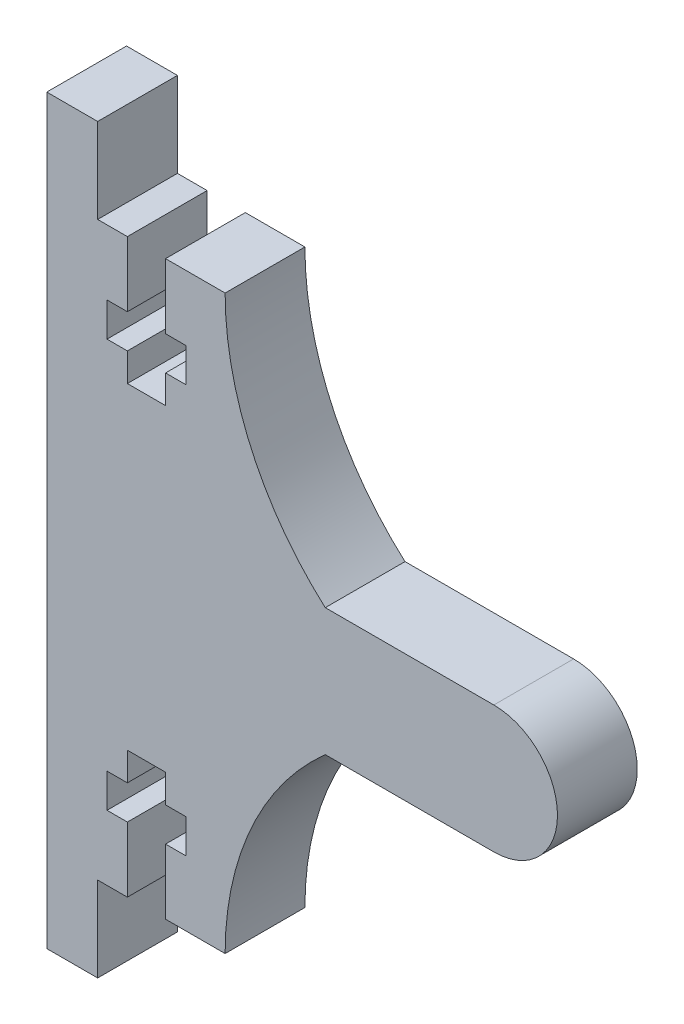
SolidWorks part; units mm, degrees
material "Acrylic (Medium-high impact)"
ref_plane "Front Plane" through (0, 0, 0) normal (0, 0, 1) x (1, 0, 0)
ref_plane "Top Plane" through (0, 0, 0) normal (0, 1, 0) x (1, 0, 0)
ref_plane "Right Plane" through (0, 0, 0) normal (1, 0, 0) x (0, 0, -1)
sketch "Sketch1" plane through (0, 0, 0) normal (0, 0, 1) x (1, 0, 0)
  line L0 (652.8999, 449.103) -> (640.9814, 449.103)
  line L1 (652.8999, 440.103) -> (640.9814, 440.103)
  line L2 (633.8999, 464.828) -> (633.8999, 424.378) construction
  line L3 (629.6883, 424.378) -> (633.8999, 424.378)
  line L4 (629.6883, 428.978) -> (629.6883, 424.378)
  line L5 (631.1282, 428.978) -> (629.6883, 428.978)
  line L6 (631.1282, 431.378) -> (631.1282, 428.978)
  line L7 (629.6883, 431.378) -> (631.1282, 431.378)
  line L8 (629.6883, 433.378) -> (629.6883, 431.378)
  line L9 (626.9883, 433.378) -> (629.6883, 433.378)
  line L10 (626.9883, 431.378) -> (626.9883, 433.378)
  line L11 (625.5484, 431.378) -> (626.9883, 431.378)
  line L12 (625.5484, 428.978) -> (625.5484, 431.378)
  line L13 (626.9883, 428.978) -> (625.5484, 428.978)
  line L14 (626.9883, 424.378) -> (626.9883, 428.978)
  line L15 (624.8883, 424.378) -> (626.9883, 424.378)
  line L16 (624.8883, 418.378) -> (624.8883, 424.378)
  line L17 (621.2883, 464.828) -> (621.2883, 470.828)
  line L18 (621.2883, 470.828) -> (624.8883, 470.828)
  line L19 (624.8883, 470.828) -> (624.8883, 464.828)
  line L20 (624.8883, 464.828) -> (626.9883, 464.828)
  line L21 (626.9883, 464.828) -> (626.9883, 460.228)
  line L22 (626.9883, 460.228) -> (625.5484, 460.228)
  line L23 (625.5484, 460.228) -> (625.5484, 457.8279)
  line L24 (625.5484, 457.8279) -> (626.9883, 457.8279)
  line L25 (626.9883, 457.8279) -> (626.9883, 455.8279)
  line L26 (626.9883, 455.8279) -> (629.6883, 455.8279)
  line L27 (629.6883, 455.8279) -> (629.6883, 457.8279)
  line L28 (629.6883, 457.8279) -> (631.1282, 457.8279)
  line L29 (631.1282, 457.8279) -> (631.1282, 460.228)
  line L30 (631.1282, 460.228) -> (629.6883, 460.228)
  line L31 (629.6883, 460.228) -> (629.6883, 464.828)
  line L32 (629.6883, 464.828) -> (633.8999, 464.828)
  line L33 (621.2883, 418.378) -> (624.8883, 418.378)
  line L34 (-348.8277, 444.603) -> (49651.1723, 444.603) construction
  line L35 (628.3383, -544.1471) -> (628.3383, 49455.8529) construction
  line L36 (621.2883, 424.378) -> (621.2883, 418.378)
  line L38 (652.8999, 449.103) -> (652.8999, 440.103) construction
  line L39 (621.2883, 464.828) -> (621.2883, 424.378)
  line L40 (633.8999, 440.103) -> (652.8999, 440.103) construction
  line L41 (633.8999, 449.103) -> (652.8999, 449.103) construction
  arc A0 (633.8999, 464.828) -> (640.9814, 449.103) centre (654.8999, 464.828) ccw
  arc A1 (633.8999, 424.378) -> (640.9814, 440.103) centre (654.8999, 424.378) cw
  arc A2 (652.8999, 440.103) -> (652.8999, 449.103) centre (652.8999, 444.603) ccw
  point P7 (640.8999, 444.603)
  point P47 (628.3383, 433.378)
  point P49 (621.2883, 444.603)
  point P50 (628.3383, 444.603)
  point P51 (628.3383, 455.8279)
  point P52 (657.3999, 444.603)
  dimension "D5" = 4.6
  dimension "D6" = 2.4001
  dimension "D11" = 21
  dimension "D1" = 6
  dimension "D2" = 3.6
  dimension "D3" = 20.225
  dimension "D4" = 9
  dimension "D7" = 2.1
  dimension "D8" = 2
  dimension "D9" = 2.7
  dimension "D10" = 1.4399
  dimension "D12" = 23.5
extrude "Boss-Extrude1" add sketch "Sketch1" along normal blind 5.64
